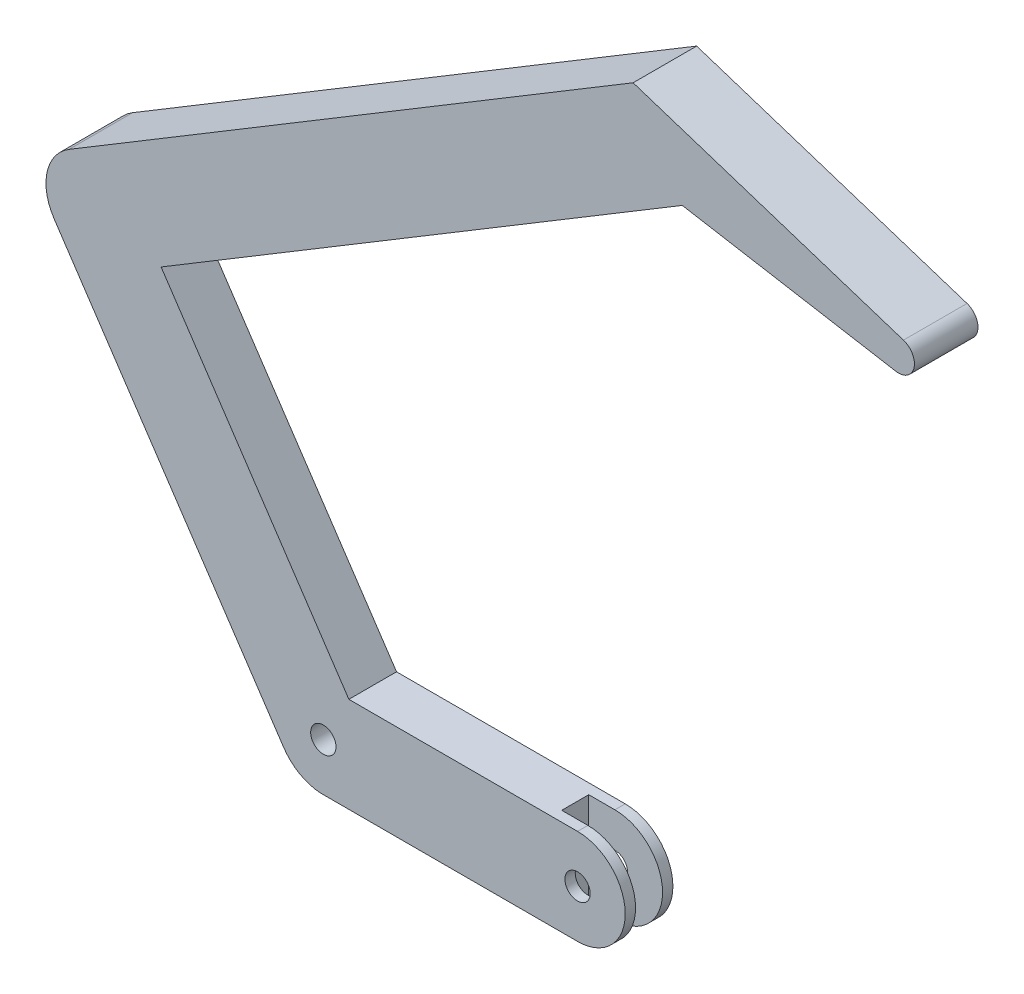
SolidWorks part; units mm, degrees
ref_plane "前视基准面" through (0, 0, 0) normal (0, 0, 1) x (1, 0, 0)
ref_plane "上视基准面" through (0, 0, 0) normal (0, 1, 0) x (1, 0, 0)
ref_plane "右视基准面" through (0, 0, 0) normal (1, 0, 0) x (0, 0, -1)
sketch "草图1" plane through (0, 0, 0) normal (0, 0, 1) x (1, 0, 0)
  line L0 (0, 0) -> (80, 0) construction
  line L1 (0, 15) -> (80, 15)
  line L2 (0, -15) -> (80, -15)
  arc A0 (0, 15) -> (0, -15) centre (0, 0) ccw
  arc A1 (80, -15) -> (80, 15) centre (80, 0) ccw
  point P3 (40, 0)
  dimension "D1" = 15
  dimension "D2" = 80
extrude "凸台-拉伸1" add sketch "草图1" along normal blind 15
sketch "草图2" plane through (0, -15, 0) normal (0, -1, 0) x (1, 0, 0)
  line L0 (0, 7.5) -> (175.9801, 7.5) construction
  line L2 (71.7692, 11.75) -> (71.7692, 3.25)
  line L3 (71.7692, 3.25) -> (95, 3.25)
  line L4 (95, 0) -> (95, 15) construction
  line L5 (95, 3.25) -> (95, 11.75)
  line L6 (95, 11.75) -> (71.7692, 11.75)
  line L7 (40, 15) -> (40, -30.3362) construction
  line L8 (0, 15) -> (80, 15) construction
  line L14 (0, 15) -> (0, 0) construction
  dimension "D2" = 8.5
extrude "切除-拉伸1" cut sketch "草图2" against normal through all both and the other way through all
sketch "草图3" plane through (0, 0, 0) normal (0, 0, -1) x (-1, 0, 0)
  line L0 (-80, 15) -> (-80, -38.2299) construction
  line L1 (-95, 0) -> (31.939, 0) construction
  arc A0 (-80, 15) -> (-80, -15) centre (-80, 0) ccw construction
  circle A1 centre (-80, 0) radius 3.985
  dimension "D1" = 7.97
extrude "切除-拉伸2" cut sketch "草图3" against normal through all both and the other way through all
sketch "草图4" plane through (0, 0, 15) normal (0, 0, 1) x (1, 0, 0)
  line L0 (-12.4828, -8.3544) -> (-84.7886, 99.682)
  line L1 (12.4828, 8.3544) -> (-59.823, 116.3908)
  arc A2 (-12.4828, -8.3544) -> (12.4828, 8.3544) centre (0, 0) ccw
  arc A3 (-59.823, 116.3908) -> (-84.7886, 99.682) centre (-72.3058, 108.0364) ccw
  dimension "D1" = 130
extrude "凸台-拉伸2" add sketch "草图4" against normal blind 15
sketch "草图9" plane through (0, 0, 0) normal (0, 0, -1) x (-1, 0, 0)
  line L0 (-80, 0) -> (0, 0) construction
  circle A0 centre (0, 0) radius 3.985
  dimension "D1" = 7.97
extrude "切除-拉伸4" cut sketch "草图9" against normal through all both and the other way through all
sketch "草图10" plane through (0, 0, 15) normal (0, 0, 1) x (1, 0, 0)
  line L5 (-84.7886, 99.682) -> (-48.2349, 123.9997)
  line L6 (-48.2349, 123.9997) -> (-59.6436, 141.149)
  line L7 (-59.6436, 141.149) -> (-100.5063, 113.9647)
  line L8 (-100.5063, 113.9647) -> (-89.0976, 96.8154)
  line L9 (-89.0976, 96.8154) -> (-84.7886, 99.682)
extrude "切除-拉伸5" cut sketch "草图10" against normal through all both and the other way through all
sketch "草图11" plane through (0, 0, 15) normal (0, 0, 1) x (1, 0, 0)
  line L0 (97.4842, 227.7487) -> (249.0111, 178.5729)
  line L3 (-64.5466, 95.1566) -> (112.9563, 202.0585)
  line L4 (-84.7886, 99.682) -> (-59.7766, 116.3214) construction
  line L5 (-80.0186, 120.8469) -> (97.4842, 227.7487)
  line L9 (249.0111, 178.5729) -> (112.9563, 202.0585)
  arc A2 (-80.0186, 120.8469) -> (-64.5466, 95.1566) centre (-72.2826, 108.0017) ccw
  point P1 (248.2073, 283.2)
  point P4 (201.9228, 253.264)
  point P9 (181.9401, 243.1475)
  point P10 (237.3424, 265.0649)
  point P11 (268.6018, 252.3086)
  point P13 (267.6581, 236.0304)
  point P14 (112.9563, 202.0585)
extrude "凸台-拉伸5" add sketch "草图11" against normal blind 20
fillet "圆角1" radius 5 1 edges at (249.0111, 178.5729, 5)
